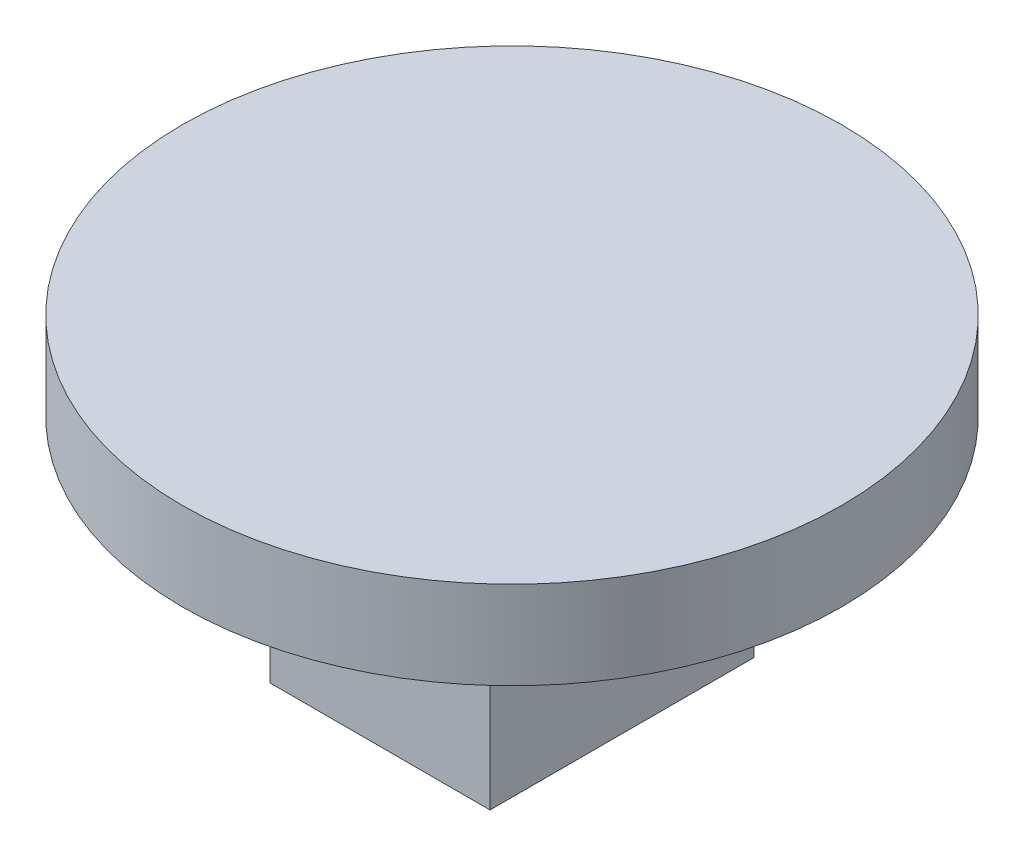
SolidWorks part; units mm, degrees
ref_plane "Front Plane" through (0, 0, 0) normal (0, 0, 1) x (1, 0, 0)
ref_plane "Top Plane" through (0, 0, 0) normal (0, 1, 0) x (1, 0, 0)
ref_plane "Right Plane" through (0, 0, 0) normal (1, 0, 0) x (0, 0, -1)
sketch "Sketch1" plane through (0, 0, 0) normal (0, 1, 0) x (1, 0, 0)
  line L1 (0, 0) -> (5, 0)
  line L2 (0, 0) -> (0, 6)
  line L3 (0, 6) -> (5, 6)
  line L4 (5, 0) -> (5, 6)
  dimension "D1" = 5
  dimension "D2" = 6
extrude "Boss-Extrude1" add sketch "Sketch1" along normal blind 5
sketch "Sketch2" plane through (0, 0, 0) normal (0, -1, 0) x (1, 0, 0)
  line L0 (0, 0) -> (5, 0) construction
  line L1 (0.875, -0.875) -> (4.125, -0.875)
  line L2 (0.875, -0.875) -> (0.875, -5.125)
  line L3 (0.875, -5.125) -> (4.125, -5.125)
  line L4 (4.125, -0.875) -> (4.125, -5.125)
  line L7 (0, -6) -> (0, 0) construction
  dimension "D1" = 3.25
  dimension "D2" = 4.25
  dimension "D3" = 0.875
  dimension "D4" = 0.875
extrude "Cut-Extrude1" cut sketch "Sketch2" against normal blind 5
sketch "Sketch3" plane through (0, 5, 0) normal (0, 1, 0) x (1, 0, 0)
  line L2 (0, 6) -> (0, 0) construction
  circle A0 centre (2.5, 3) radius 7.5
  point P5 (2.2843, 2.8137)
  dimension "D3" = 15
  dimension "D1" = 3
  dimension "D2" = 2.5
extrude "Boss-Extrude2" add sketch "Sketch3" along normal blind 2
